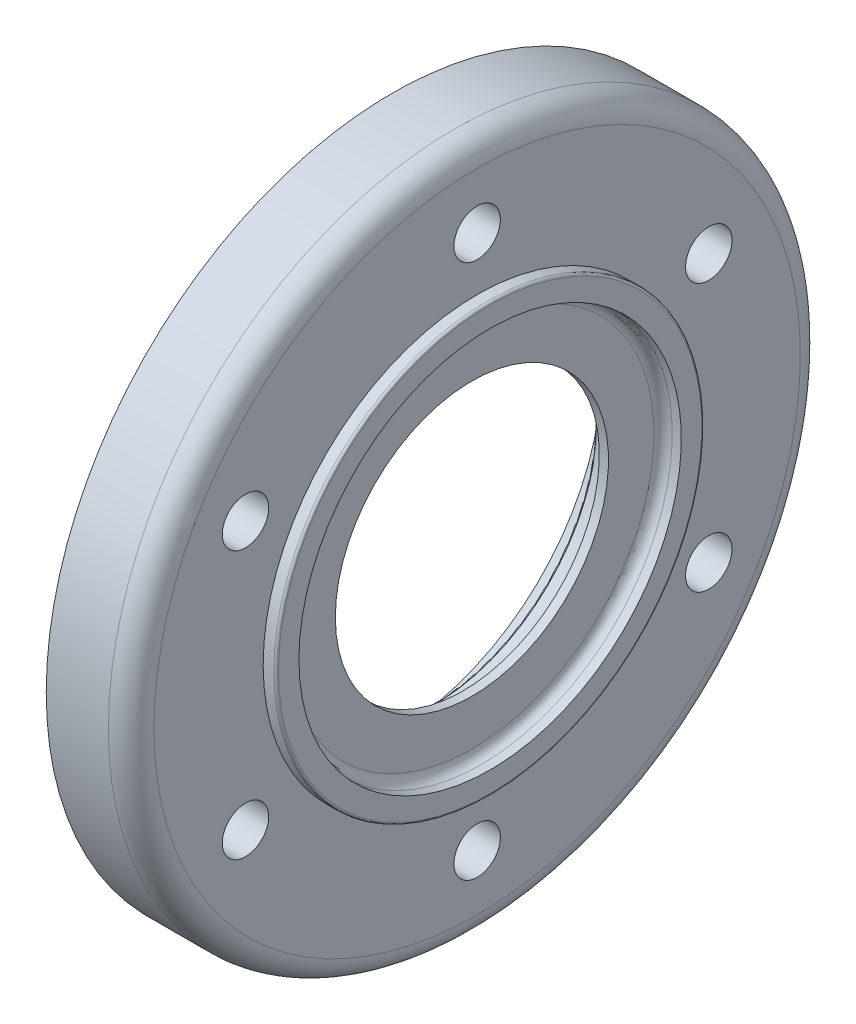
SolidWorks part; units mm, degrees
ref_plane "Front Plane" through (0, 0, 0) normal (0, 0, 1) x (1, 0, 0)
ref_plane "Top Plane" through (0, 0, 0) normal (0, 1, 0) x (1, 0, 0)
ref_plane "Right Plane" through (0, 0, 0) normal (1, 0, 0) x (0, 0, -1)
sketch "Sketch1" plane through (0, 0, 0) normal (0, 1, 0) x (1, 0, 0)
  line L0 (0.5952, 30) -> (2.5952, 30)
  line L1 (2.5952, 30) -> (2.5952, 40)
  line L2 (4.5952, 42) -> (6.5952, 42)
  line L3 (6.5952, 42) -> (6.5952, 47)
  line L7 (-2.2556, 76) -> (-2.2556, 49)
  line L8 (-5.2556, 46) -> (-6.4048, 46)
  line L9 (-6.4048, 46) -> (-6.4048, 36)
  line L10 (-6.4048, 36) -> (0.5952, 36)
  line L11 (0.5952, 36) -> (0.5952, 30)
  line L12 (6.5952, 47) -> (3.7444, 47)
  line L13 (3.7444, 47) -> (3.7444, 76)
  line L14 (3.7444, 76) -> (-2.2556, 76)
  line L16 (0, 0) -> (11.072, 0) construction
  arc A0 (-2.2556, 49) -> (-5.2556, 46) centre (-5.2556, 49) cw
  arc A1 (2.5952, 40) -> (4.5952, 42) centre (4.5952, 40) cw
  point P18 (-2.2556, 46)
  point P21 (2.5952, 42)
  dimension "D11" = 3
  dimension "D12" = 2
  dimension "D1" = 2
  dimension "D2" = 12
  dimension "D3" = 6
  dimension "D4" = 30
  dimension "D5" = 7
  dimension "D6" = 4
  dimension "D7" = 5
  dimension "D8" = 10
  dimension "D9" = 6
  dimension "D10" = 30
revolve "Revolve1" add sketch "Sketch1" angle 360 about L16
fillet "Fillet1" radius 0.5 1 edges at (-6.4048, 0, 36)
fillet "Fillet4" radius 0.5 1 edges at (6.5952, 0, 47)
sketch "Sketch2" plane through (3.7444, 0, 0) normal (1, 0, 0) x (0, 0, -1)
  circle A0 centre (0, 0) radius 76 construction
  circle A1 centre (0, 0) radius 76
  circle A2 centre (0, 0) radius 47 construction
  circle A3 centre (0, 0) radius 47
sketch "Sketch3" plane through (-2.2556, 0, 0) normal (-1, 0, 0) x (0, 0, 1)
  circle A0 centre (0, 0) radius 76 construction
  circle A1 centre (0, 0) radius 76
  circle A2 centre (0, 0) radius 46 construction
  circle A3 centre (0, 0) radius 46
extrude "Boss-Extrude2" add sketch "Sketch3" along normal blind 18.65
fillet "Fillet5" radius 5 1 edges at (3.7444, 0, 76)
hole_wizard "M12x1.75 Tapped Hole1" positions "Sketch4" profile "Sketch5" tap size "M12x1.75" standard "ANSI Metric"
sketch "Sketch4" plane through (3.7444, 0, 0) normal (1, 0, 0) x (0, 0, -1)
  line L0 (0, 71) -> (0, 46.5) construction
  circle A0 centre (0, 0) radius 71 construction
  circle A1 centre (0, 0) radius 46.5 construction
  point P0 (0, 58.75)
  point P15 (0, 58.75)
  point P19 (50.879, 29.375)
  point P20 (50.879, -29.375)
  point P21 (0, -58.75)
  point P22 (-50.879, -29.375)
  point P23 (-50.879, 29.375)
sketch "Sketch5" plane through (3.7444, 58.75, 0) normal (0, 1, 0) x (0, 0, -1)
  line L0 (0, 0) -> (0, 32.3144)
  line L1 (0, 32.3144) -> (5.1, 29.25)
  line L2 (5.1, 29.25) -> (5.1, 0)
  line L5 (5.1, 0) -> (0, 0)
  line L10 (0, 32.3144) -> (-5.1, 29.25) construction
  line L11 (0, -6.35) -> (0, 107.95) construction
  dimension "Tap Drill Dia." = 10.2
  dimension "Tap Drill Depth" = 29.25
  dimension "Drill Angle" = 118
cosmetic thread "Hole Thread1" parameters "D1"=24, "D2"=12
cosmetic thread "Hole Thread2" parameters "D1"=24, "D2"=12
cosmetic thread "Hole Thread3" parameters "D1"=24, "D2"=12
cosmetic thread "Hole Thread4" parameters "D1"=24, "D2"=12
cosmetic thread "Hole Thread5" parameters "D1"=24, "D2"=12
cosmetic thread "Hole Thread6" parameters "D1"=24, "D2"=12
sketch "Sketch6" plane through (0, 0, 0) normal (0, 1, 0) x (1, 0, 0)
  line L0 (-14.9048, -320.9422) -> (-14.9048, 226.2337) construction
  line L1 (-20.9056, 76) -> (-14.9048, 76)
  line L2 (-20.9056, 76) -> (-20.9056, -76)
  line L3 (-20.9056, -76) -> (-14.9048, -76)
  line L4 (-14.9048, 76) -> (-14.9048, -76)
  point P5 (0, 0)
extrude "Cut-Extrude2" cut sketch "Sketch6" against normal mid plane 198
